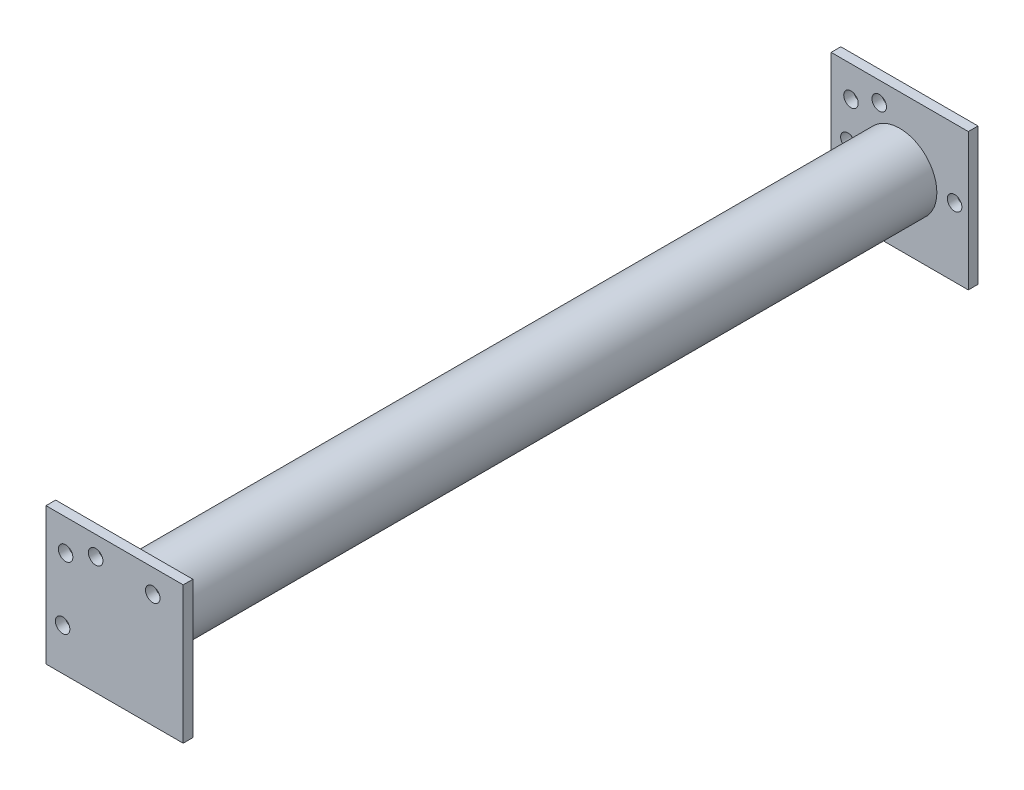
SolidWorks part; units mm, degrees
ref_plane "Front Plane" through (0, 0, 0) normal (0, 0, 1) x (1, 0, 0)
ref_plane "Top Plane" through (0, 0, 0) normal (0, 1, 0) x (1, 0, 0)
ref_plane "Right Plane" through (0, 0, 0) normal (1, 0, 0) x (0, 0, -1)
sketch "Sketch1" plane through (0, 0, 0) normal (0, 0, 1) x (1, 0, 0)
  circle A0 centre (0, 0) radius 46
  circle A1 centre (0, 0) radius 40
  dimension "D1" = 80
  dimension "D2" = 92
extrude "Boss-Extrude1" add sketch "Sketch1" along normal blind 961
sketch "Sketch2" plane through (0, 0, 0) normal (0, 0, -1) x (-1, 0, 0)
  line L1 (-85, 85) -> (85, 85)
  line L2 (-85, 85) -> (-85, -85)
  line L3 (-85, -85) -> (85, -85)
  line L4 (85, 85) -> (85, -85)
  circle A0 centre (64.2276, 0) radius 9
  circle A1 centre (-68.0305, 0) radius 9
  circle A2 centre (60.408, 46.8966) radius 9
  circle A3 centre (25.4168, 60.6636) radius 9
  dimension "D5" = 18
  dimension "D6" = 18
  dimension "D7" = 18
  dimension "D8" = 18
  dimension "D1" = 170
  dimension "D2" = 170
  dimension "D3" = 85
  dimension "D4" = 85
extrude "Boss-Extrude2" add sketch "Sketch2" along normal blind 12
sketch "Sketch3" plane through (0, 0, 961) normal (0, 0, 1) x (1, 0, 0)
  line L1 (-85, 85) -> (85, 85)
  line L2 (-85, 85) -> (-85, -85)
  line L3 (-85, -85) -> (85, -85)
  line L4 (85, 85) -> (85, -85)
  line L8 (-120.6872, 0) -> (109.8433, 0) construction
  line L10 (0, 65.5765) -> (0, -62.7375) construction
  circle A6 centre (47.3067, 56.0603) radius 9
  circle A7 centre (-23.4671, 60.9027) radius 9
  circle A8 centre (-60.7165, 46.2262) radius 9
  circle A9 centre (-64.4414, -32.9657) radius 9
  dimension "D5" = 18
  dimension "D6" = 18
  dimension "D7" = 18
  dimension "D8" = 18
  dimension "D1" = 170
  dimension "D2" = 170
  dimension "D3" = 85
  dimension "D4" = 85
extrude "Boss-Extrude3" add sketch "Sketch3" along normal blind 12
